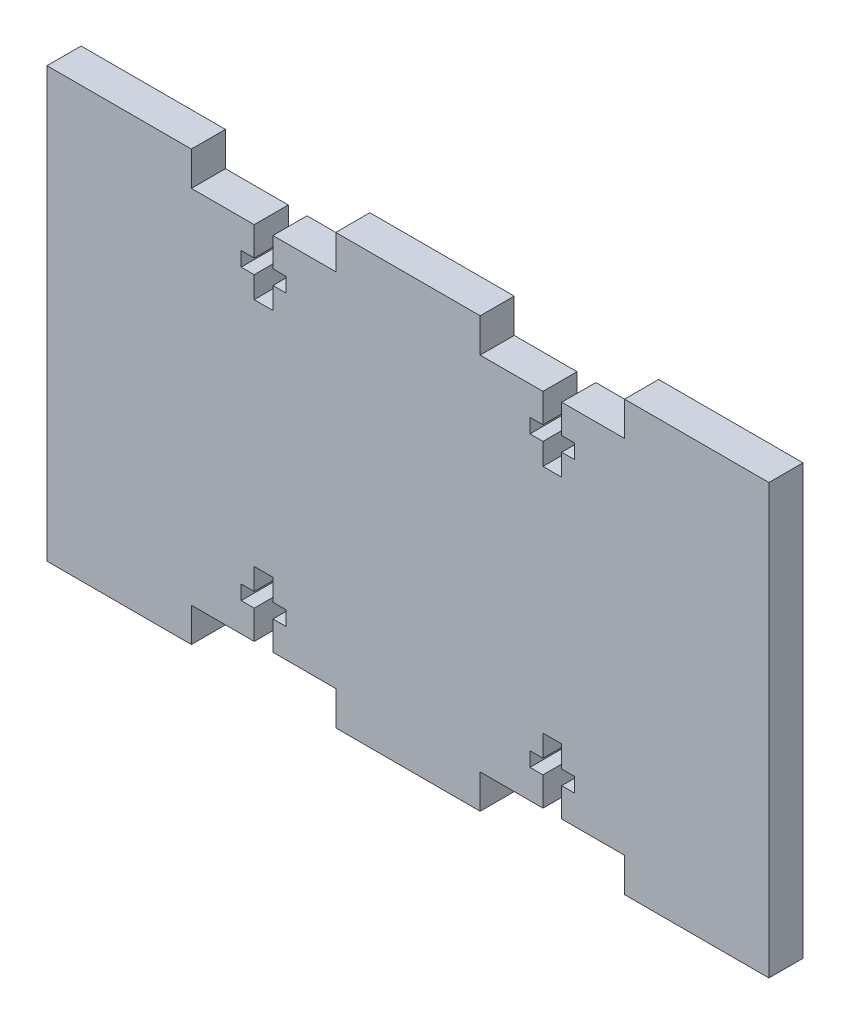
SolidWorks part; units mm, degrees
ref_plane "Front Plane" through (0, 0, 0) normal (0, 0, 1) x (1, 0, 0)
ref_plane "Top Plane" through (0, 0, 0) normal (0, 1, 0) x (1, 0, 0)
ref_plane "Right Plane" through (0, 0, 0) normal (1, 0, 0) x (0, 0, -1)
sketch "Sketch1" plane through (0, 0, 0) normal (0, 0, 1) x (1, 0, 0)
  line L0 (63.5, 75.4888) -> (63.5, 0) construction
  line L1 (25.4, 5.9944) -> (50.8, 5.9944)
  line L2 (0, 0) -> (0, 75.4888)
  line L3 (25.4, 69.4944) -> (50.8, 69.4944)
  line L4 (127, 0) -> (127, 75.4888)
  line L5 (76.2, 69.4944) -> (101.6, 69.4944)
  line L6 (127, 37.7444) -> (0, 37.7444) construction
  line L7 (0, 75.4888) -> (25.4, 75.4888)
  line L8 (25.4, 69.4944) -> (25.4, 75.4888)
  line L9 (101.6, 69.4944) -> (101.6, 75.4888)
  line L10 (50.8, 69.4944) -> (50.8, 75.4888)
  line L11 (50.8, 75.4888) -> (76.2, 75.4888)
  line L12 (76.2, 69.4944) -> (76.2, 75.4888)
  line L13 (127, 75.4888) -> (101.6, 75.4888)
  line L14 (127, 0) -> (101.6, 0)
  line L15 (76.2, 5.9944) -> (76.2, 0)
  line L16 (50.8, 0) -> (76.2, 0)
  line L17 (50.8, 5.9944) -> (50.8, 0)
  line L18 (101.6, 5.9944) -> (101.6, 0)
  line L19 (25.4, 5.9944) -> (25.4, 0)
  line L20 (0, 0) -> (25.4, 0)
  line L21 (76.2, 5.9944) -> (101.6, 5.9944)
  dimension "D1" = 25.4
  dimension "D2" = 25.4
  dimension "D3" = 127
  dimension "D4" = 5.9944
  dimension "D6" = 31.75
extrude "Boss-Extrude1" add sketch "Sketch1" along normal blind 5.9944
sketch "Sketch2" plane through (0, 0, 5.9944) normal (0, 0, 1) x (1, 0, 0)
  line L0 (63.5, 75.4888) -> (63.5, 0) construction
  line L1 (76.2, 75.4888) -> (50.8, 75.4888) construction
  line L2 (50.8, 0) -> (76.2, 0) construction
  line L3 (36.449, 69.4944) -> (36.449, 64.4144)
  line L4 (50.8, 69.4944) -> (25.4, 69.4944) construction
  line L5 (36.449, 64.4144) -> (34.163, 64.4144)
  line L6 (34.163, 64.4144) -> (34.163, 61.8744)
  line L7 (34.163, 61.8744) -> (36.449, 61.8744)
  line L8 (36.449, 61.8744) -> (36.449, 58.0644)
  line L9 (36.449, 58.0644) -> (39.751, 58.0644)
  line L10 (39.751, 58.0644) -> (39.751, 61.8744)
  line L11 (39.751, 61.8744) -> (42.037, 61.8744)
  line L12 (42.037, 61.8744) -> (42.037, 64.4144)
  line L13 (42.037, 64.4144) -> (39.751, 64.4144)
  line L14 (39.751, 64.4144) -> (39.751, 69.4944)
  line L15 (36.449, 69.4944) -> (39.751, 69.4944)
  line L16 (0, 37.7444) -> (127, 37.7444) construction
  line L17 (0, 75.4888) -> (0, 0) construction
  line L18 (127, 0) -> (127, 75.4888) construction
  line L19 (36.449, 5.9944) -> (39.751, 5.9944)
  line L20 (39.751, 11.0744) -> (39.751, 5.9944)
  line L21 (42.037, 11.0744) -> (39.751, 11.0744)
  line L22 (42.037, 13.6144) -> (42.037, 11.0744)
  line L23 (39.751, 13.6144) -> (42.037, 13.6144)
  line L24 (39.751, 17.4244) -> (39.751, 13.6144)
  line L25 (36.449, 17.4244) -> (39.751, 17.4244)
  line L26 (36.449, 13.6144) -> (36.449, 17.4244)
  line L27 (34.163, 13.6144) -> (36.449, 13.6144)
  line L28 (34.163, 11.0744) -> (34.163, 13.6144)
  line L29 (36.449, 11.0744) -> (34.163, 11.0744)
  line L30 (36.449, 5.9944) -> (36.449, 11.0744)
  line L31 (90.551, 5.9944) -> (90.551, 11.0744)
  line L32 (90.551, 11.0744) -> (92.837, 11.0744)
  line L33 (92.837, 11.0744) -> (92.837, 13.6144)
  line L34 (92.837, 13.6144) -> (90.551, 13.6144)
  line L35 (90.551, 13.6144) -> (90.551, 17.4244)
  line L36 (90.551, 17.4244) -> (87.249, 17.4244)
  line L37 (87.249, 17.4244) -> (87.249, 13.6144)
  line L38 (87.249, 13.6144) -> (84.963, 13.6144)
  line L39 (84.963, 13.6144) -> (84.963, 11.0744)
  line L40 (84.963, 11.0744) -> (87.249, 11.0744)
  line L41 (87.249, 11.0744) -> (87.249, 5.9944)
  line L42 (90.551, 5.9944) -> (87.249, 5.9944)
  line L43 (90.551, 69.4944) -> (87.249, 69.4944)
  line L44 (87.249, 64.4144) -> (87.249, 69.4944)
  line L45 (84.963, 64.4144) -> (87.249, 64.4144)
  line L46 (84.963, 61.8744) -> (84.963, 64.4144)
  line L47 (87.249, 61.8744) -> (84.963, 61.8744)
  line L48 (87.249, 58.0644) -> (87.249, 61.8744)
  line L49 (90.551, 58.0644) -> (87.249, 58.0644)
  line L50 (90.551, 61.8744) -> (90.551, 58.0644)
  line L51 (92.837, 61.8744) -> (90.551, 61.8744)
  line L52 (92.837, 64.4144) -> (92.837, 61.8744)
  line L53 (90.551, 64.4144) -> (92.837, 64.4144)
  line L54 (90.551, 69.4944) -> (90.551, 64.4144)
  point P10 (38.1, 69.4944)
  point P22 (38.1, 69.4944)
  point P40 (38.1, 5.9944)
  point P65 (88.9, 5.9944)
  point P66 (88.9, 69.4944)
  dimension "D1" = 3.302
  dimension "D2" = 11.43
  dimension "D3" = 2.286
  dimension "D4" = 2.54
  dimension "D5" = 5.08
extrude "Cut-Extrude2" cut sketch "Sketch2" against normal blind 5.9944
